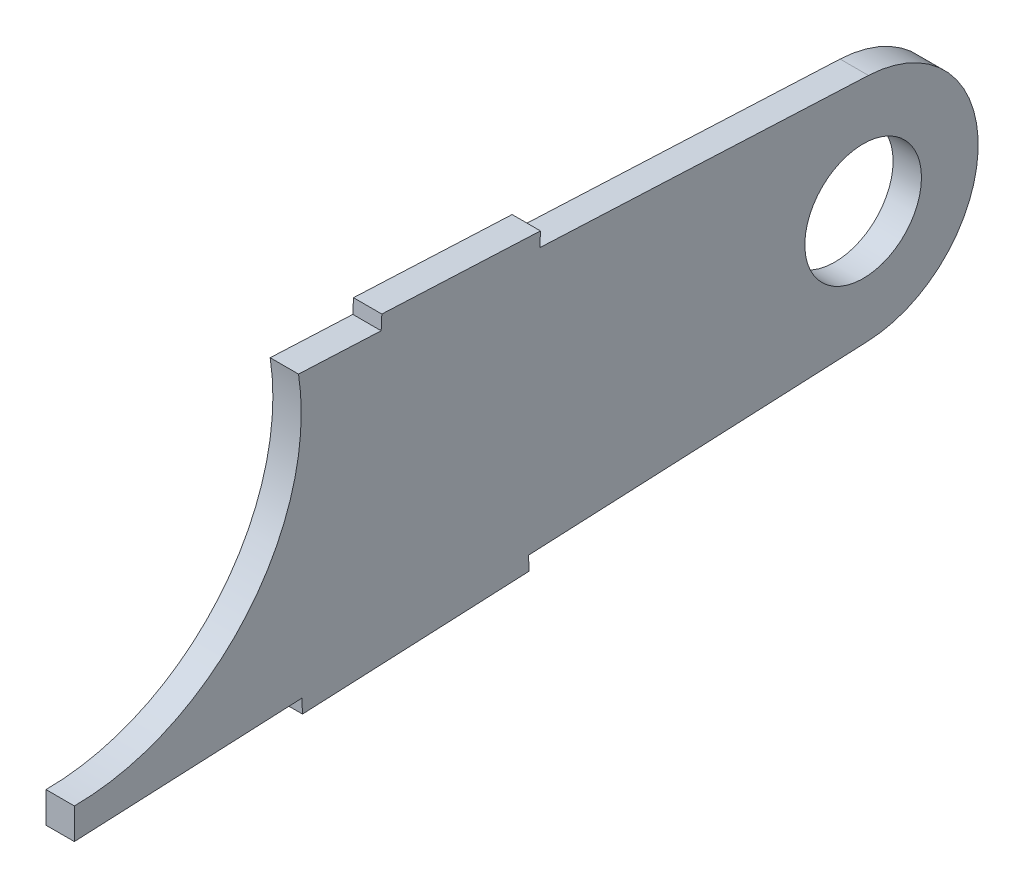
SolidWorks part; units mm, degrees
material "AISI 4130 Steel, annealed at 865C"
ref_plane "X-Y Datum" through (0, 0, 0) normal (0, 0, 1) x (1, 0, 0)
ref_plane "X-Z Datum" through (0, 0, 0) normal (0, 1, 0) x (1, 0, 0)
ref_plane "Y-Z Datum" through (0, 0, 0) normal (1, 0, 0) x (0, 0, -1)
sketch "Sketch1" plane through (0, 0, 0) normal (1, 0, 0) x (0, 0, -1)
  line L0 (0, 0) -> (-66.675, 0) construction
  line L1 (-66.675, 9.525) -> (-66.675, -9.525)
  line L2 (0.297, 6.432) -> (-66.675, 9.525)
  line L3 (0.297, -6.432) -> (-66.675, -9.525)
  line L4 (-31.3825, -8.6897) -> (-18.696, -8.1038)
  line L5 (-31.3825, -8.6897) -> (-31.4558, -7.1039)
  line L6 (-18.696, -8.1038) -> (-18.7693, -6.518)
  line L7 (-31.4558, -7.1039) -> (-18.7693, -6.518)
  line L8 (-31.3825, -8.6897) -> (-18.7693, -6.518) construction
  line L9 (-18.696, -8.1038) -> (-31.4558, -7.1039) construction
  line L10 (-44.153, 8.4849) -> (-44.153, 5.9449)
  line L11 (0.297, -6.432) -> (-44.153, -8.4849)
  line L12 (-27.0155, 6.8988) -> (-18.135, 6.4887)
  line L13 (-27.0155, 6.8988) -> (-26.9423, 8.4846)
  line L14 (-18.135, 6.4887) -> (-18.0617, 8.0745)
  line L15 (-26.9423, 8.4846) -> (-18.0617, 8.0745)
  line L16 (-27.0155, 6.8988) -> (-18.0617, 8.0745) construction
  line L17 (-18.135, 6.4887) -> (-26.9423, 8.4846) construction
  line L18 (-44.153, -8.4849) -> (-44.153, 8.4849)
  circle A0 centre (0, 0) radius 3.2639
  arc A1 (0.297, -6.432) -> (0.297, 6.432) centre (0, 0) ccw
  circle A3 centre (-44.153, 5.9449) radius 12.7
  point P7 (-66.675, 0)
  point P10 (-22.3404, -7.1328)
  point P17 (-25.0759, -7.6038)
  point P18 (-22.5386, 7.4867)
  dimension "D1" = 6.5278
  dimension "D2" = 3.175
  dimension "D9" = 25.4
  dimension "D3" = 66.675
  dimension "D4" = 19.05
  dimension "D5" = 12.7
  dimension "D6" = 1.5875
  dimension "D7" = 19.05
  dimension "D8" = 44.45
  dimension "D10" = 2.54
  dimension "D11" = 1.5875
  dimension "D12" = 22.86
  dimension "D13" = 8.89
extrude "Boss-Extrude1" add sketch "Sketch1" along normal mid plane 1.5875 contours L3 A1 L2 L1 L5 L7 L6 A0 | L7 L5 L3 L6 | L4 L6 L3 L5 | L12 L14 L2 L13 | L15 L13 L2 L14
